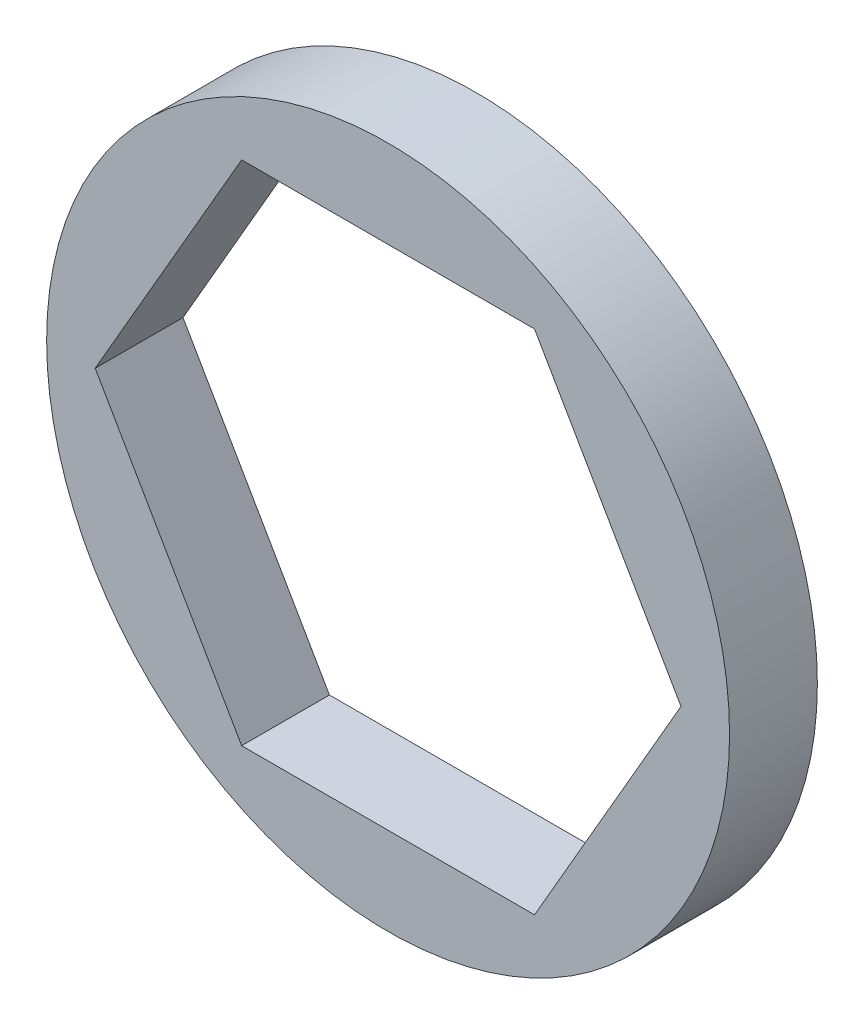
SolidWorks part; units mm, degrees
material "ABS PC"
ref_plane "Front Plane" through (0, 0, 0) normal (0, 0, 1) x (1, 0, 0)
ref_plane "Top Plane" through (0, 0, 0) normal (0, 1, 0) x (1, 0, 0)
ref_plane "Right Plane" through (0, 0, 0) normal (1, 0, 0) x (0, 0, -1)
sketch "Sketch3" plane through (0, 0, 0) normal (0, 0, 1) x (1, 0, 0)
  line L1 (7.6256, 0) -> (3.8128, 6.604)
  line L2 (3.8128, 6.604) -> (-3.8128, 6.604)
  line L3 (-3.8128, 6.604) -> (-7.6256, 0)
  line L4 (-7.6256, 0) -> (-3.8128, -6.604)
  line L5 (-3.8128, -6.604) -> (3.8128, -6.604)
  line L6 (3.8128, -6.604) -> (7.6256, 0)
  circle A0 centre (0, 0) radius 8.89
  circle A1 centre (0, 0) radius 6.604 construction
  dimension "D1" = 13.208
  dimension "D2" = 17.78
extrude "Boss-Extrude2" add sketch "Sketch3" along normal blind 2.286
ref_plane "Plane2" through (0, 8.89, 0) normal (0, 1, 0) x (1, 0, 0)
sketch "Sketch4" plane through (0, 8.89, 0) normal (0, 1, 0) x (1, 0, 0)
  line L0 (-8.89, -2.915) -> (8.89, -2.915) construction
  line L3 (-8.89, -1.143) -> (-8.89, -2.915) construction
  line L4 (-8.89, 0) -> (-8.89, -2.286) construction
  text T0 "0.090000"
  dimension "D1" = 1.772
wrap "Wrap2" [suppressed] sketch "Sketch4" source sketch "Sketch4" thickness 0.508 parameters "D1"=0.508
equation "\"Length\"= .09in"
equation "\"D1@Boss-Extrude2\"=\"Length\""
